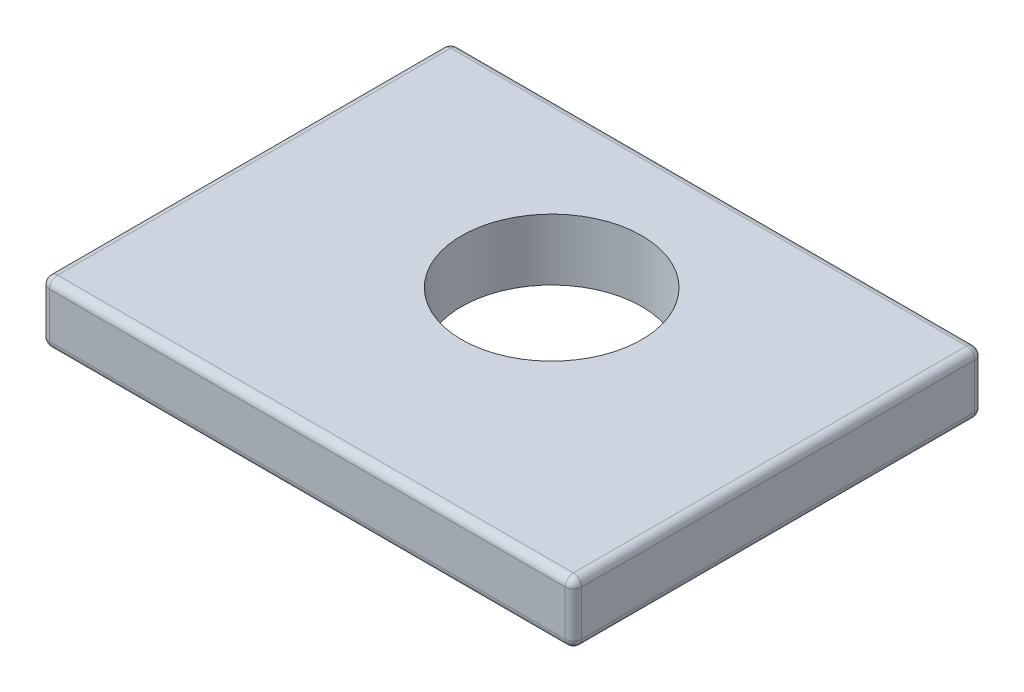
SolidWorks part; units mm, degrees
material "Windform LX 3.0"
ref_plane "Front Plane" through (0, 0, 0) normal (0, 0, 1) x (1, 0, 0)
ref_plane "Top Plane" through (0, 0, 0) normal (0, 1, 0) x (1, 0, 0)
ref_plane "Right Plane" through (0, 0, 0) normal (1, 0, 0) x (0, 0, -1)
sketch "Sketch1" plane through (0, 0, 0) normal (0, 1, 0) x (1, 0, 0)
  line L1 (-3.25, -2.5) -> (3.25, -2.5)
  line L2 (-3.25, -2.5) -> (-3.25, 2.5)
  line L3 (-3.25, 2.5) -> (3.25, 2.5)
  line L4 (3.25, -2.5) -> (3.25, 2.5)
  line L5 (-3.25, -2.5) -> (3.25, 2.5) construction
  line L6 (-3.25, 2.5) -> (3.25, -2.5) construction
  point P0 (0, 0)
  dimension "D1" = 6.5
  dimension "D2" = 5
extrude "Boss-Extrude1" add sketch "Sketch1" along normal blind 0.75
sketch "Sketch2" plane through (0, 0, 0) normal (0, 1, 0) x (1, 0, 0)
  circle A0 centre (0, 0.4847) radius 2.653 construction
  circle A1 centre (0, 0.4847) radius 2.653 construction
  circle A2 centre (0, 0.4847) radius 1.1
  dimension "D1" = 2.2
extrude "Cut-Extrude1" cut sketch "Sketch2" along normal through all
fillet "Fillet1" radius 0.1 12 edges at (3.25, 0.75, 0) (3.25, 0, 0) (0, 0.75, 2.5) (3.25, 0.375, 2.5) (0, 0, 2.5) (-3.25, 0.75, 0) (-3.25, 0.375, 2.5) (-3.25, 0, 0) (3.25, 0.375, -2.5) (0, 0.75, -2.5) (-3.25, 0.375, -2.5) (0, 0, -2.5)
